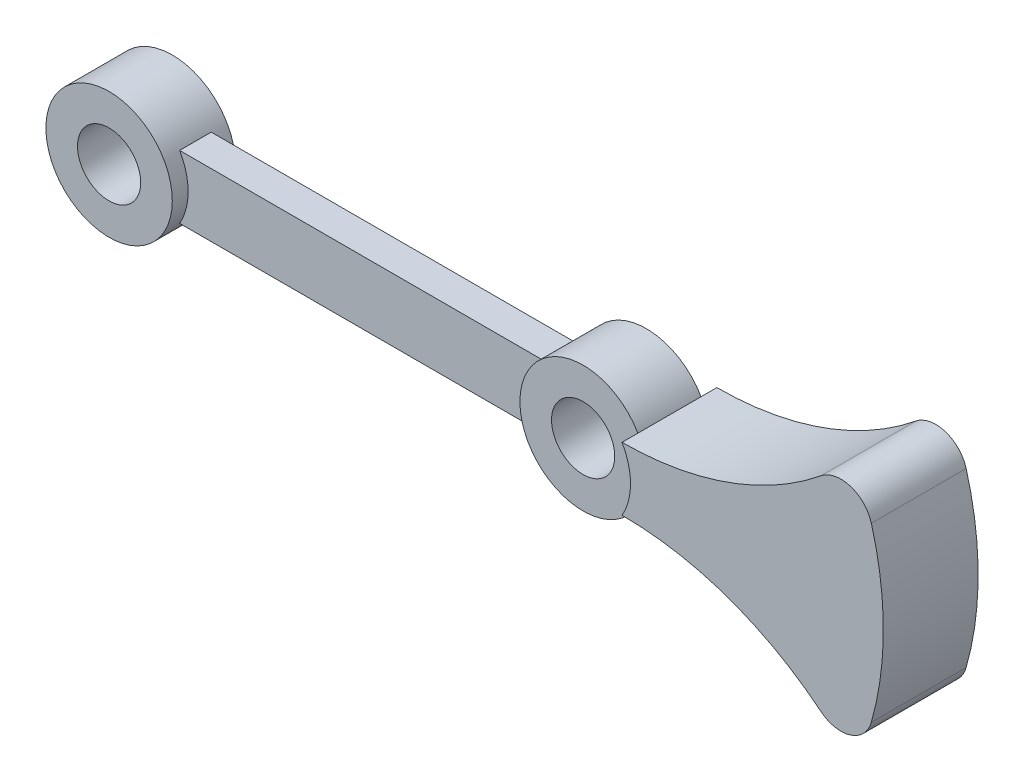
SolidWorks part; units mm, degrees
ref_plane "Front Plane" through (0, 0, 0) normal (0, 0, 1) x (1, 0, 0)
ref_plane "Top Plane" through (0, 0, 0) normal (0, 1, 0) x (1, 0, 0)
ref_plane "Right Plane" through (0, 0, 0) normal (1, 0, 0) x (0, 0, -1)
sketch "Sketch1" plane through (0, 0, 0) normal (0, 0, 1) x (1, 0, 0)
  line L0 (45, 0) -> (-45, 0) construction
  circle A0 centre (-45, 0) radius 12
  circle A1 centre (45, 0) radius 12
  circle A2 centre (-45, 0) radius 6
  circle A3 centre (45, 0) radius 6
  point P4 (0, 0)
  dimension "Diam_P" = 12
  dimension "D1" = 24
  dimension "D3" = 12
  dimension "D4" = 24
  dimension "D2" = 90
extrude "Boss-Extrude1" add sketch "Sketch1" against normal mid plane 12
sketch "Sketch3" plane through (0, 0, 0) normal (0, 0, 1) x (1, 0, 0)
  line L0 (-34.6077, 6) -> (34.6077, 6)
  line L1 (-34.6077, -6) -> (34.6077, -6)
  line L2 (0, -6) -> (0, 6) construction
  circle A0 centre (-45, 0) radius 12 construction
  circle A1 centre (45, 0) radius 12 construction
  arc A2 (34.6077, 6) -> (34.6077, -6) centre (45, 0) ccw
  arc A3 (-34.6077, -6) -> (-34.6077, 6) centre (-45, 0) ccw
  point P14 (0, 0)
  dimension "D1" = 12
extrude "Boss-Extrude2" add sketch "Sketch3" along normal mid plane 6
sketch "Sketch4" plane through (0, 0, 0) normal (0, 0, 1) x (1, 0, 0)
  line L0 (34.6077, 6) -> (55.3923, 6) construction
  line L1 (55.3923, 6) -> (55.3923, -6) construction
  circle A0 centre (45, 0) radius 12 construction
  arc A1 (55.3923, 6) -> (93.1743, 19.3897) centre (55.3923, 66) ccw
  arc A2 (55.3923, -6) -> (93.1743, -19.3897) centre (55.3923, -66) cw
  arc A3 (102.725, 16.3652) -> (102.725, -16.3652) centre (45, 0) cw
  arc A4 (93.1743, 19.3897) -> (102.725, 16.3652) centre (96.9525, 14.7287) cw
  arc A5 (102.725, -16.3652) -> (93.1743, -19.3897) centre (96.9525, -14.7287) cw
  arc A6 (55.3923, -6) -> (55.3923, 6) centre (45, 0) ccw
  dimension "D1" = 60
  dimension "D2" = 60
  dimension "D3" = 6
  dimension "D4" = 60
extrude "Boss-Extrude3" add sketch "Sketch4" along normal mid plane 18
equation "\"Diam\"=12"
equation "\"Diam_P@Sketch1\"=\"Diam\""
equation "\"D1@Sketch1\"=\"Diam\"*2"
equation "\"D2@Sketch1\"=\"Diam\"*7.5"
equation "\"D3@Sketch1\"=\"Diam\""
equation "\"D4@Sketch1\"=\"Diam\"*2"
equation "\"D1@Sketch4\"=\"Diam\"*5"
equation "\"D2@Sketch4\"=\"Diam\"*5"
equation "\"D4@Sketch4\"=\"Diam\"*5"
equation "\"D3@Sketch4\"=\"Diam\"/2"
equation "\"D1@Boss-Extrude3\"=\"Diam\"*(18/12)"
